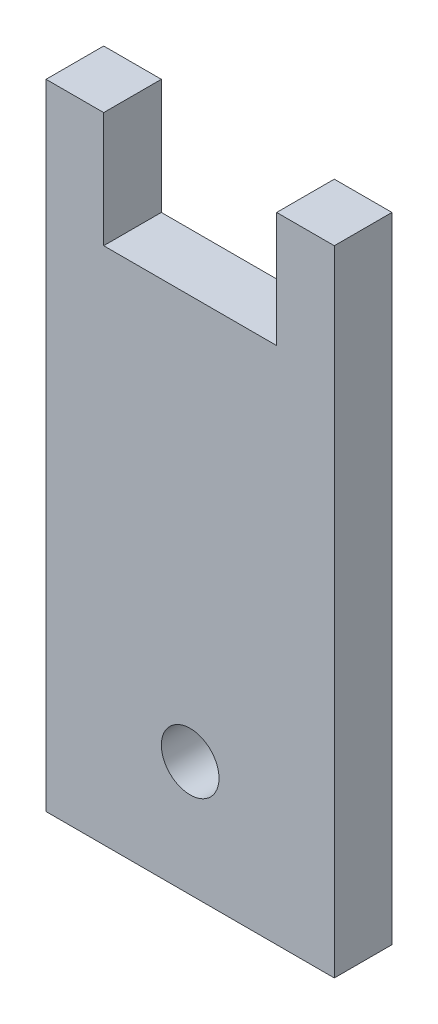
SolidWorks part; units mm, degrees
ref_plane "Front Plane" through (0, 0, 0) normal (0, 0, 1) x (1, 0, 0)
ref_plane "Top Plane" through (0, 0, 0) normal (0, 1, 0) x (1, 0, 0)
ref_plane "Right Plane" through (0, 0, 0) normal (1, 0, 0) x (0, 0, -1)
sketch "Sketch1" plane through (0, 0, 0) normal (0, 0, 1) x (1, 0, 0)
  line L0 (-7.5, 27.5) -> (-7.5, 17.5)
  line L1 (-12.5, 27.5) -> (-7.5, 27.5)
  line L2 (-12.5, 27.5) -> (-12.5, -27.5)
  line L3 (-12.5, -27.5) -> (12.5, -27.5)
  line L4 (12.5, 27.5) -> (12.5, -27.5)
  line L5 (-12.5, 27.5) -> (12.5, -27.5) construction
  line L6 (-12.5, -27.5) -> (12.5, 27.5) construction
  line L7 (-7.5, 17.5) -> (7.5, 17.5)
  line L8 (7.5, 17.5) -> (7.5, 27.5)
  line L9 (7.5, 27.5) -> (12.5, 27.5)
  point P0 (0, 0)
  dimension "D1" = 55
  dimension "D2" = 25
  dimension "D3" = 5
  dimension "D4" = 5
  dimension "D5" = 10
extrude "Boss-Extrude1" add sketch "Sketch1" along normal blind 5
sketch "Sketch2" plane through (0, 0, 5) normal (0, 0, 1) x (1, 0, 0)
  line L0 (-12.5, -27.5) -> (12.5, -27.5) construction
  circle A0 centre (0, -17.5) radius 2.5
  dimension "D1" = 5
  dimension "D2" = 10
extrude "Cut-Extrude1" cut sketch "Sketch2" against normal through all
